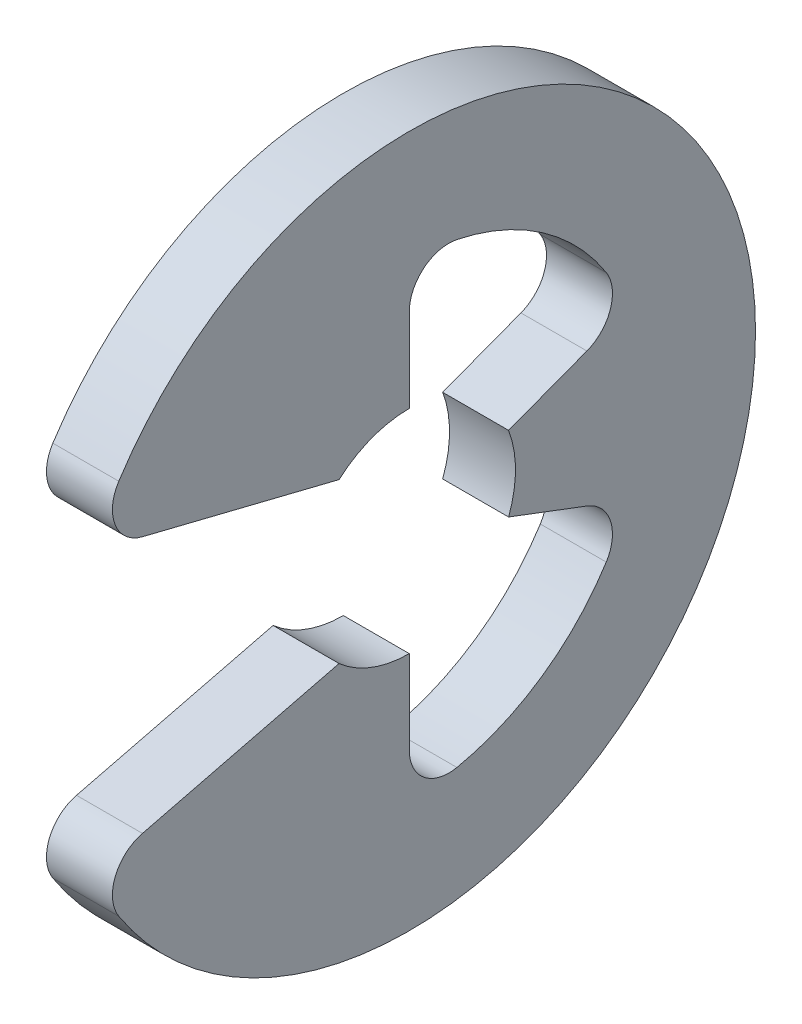
SolidWorks part; units mm, degrees
ref_plane "Front Plane" through (0, 0, 0) normal (0, 0, 1) x (1, 0, 0)
ref_plane "Top Plane" through (0, 0, 0) normal (0, 1, 0) x (1, 0, 0)
ref_plane "Right Plane" through (0, 0, 0) normal (1, 0, 0) x (0, 0, -1)
ref_plane "Plane1" through (-0.25, 0, 0) normal (-1, 0, 0) x (0, -1, 0)
sketch "Sketch1" plane through (-0.25, 0, 0) normal (-1, 0, 0) x (0, -1, 0)
  line L0 (0.9738, 2.023) -> (0.6037, 0.5325)
  line L1 (0.805, 0) -> (1.4394, 0)
  line L2 (0.5089, -1.3464) -> (0.2846, -0.753)
  line L3 (-0.2846, -0.753) -> (-0.5089, -1.3464)
  line L4 (-1.4394, 0) -> (-0.805, 0)
  line L5 (-0.6037, 0.5325) -> (-0.9738, 2.023)
  arc A0 (-1.4282, 2.2025) -> (1.4282, 2.2025) centre (0, 0) ccw
  arc A1 (1.4282, 2.2025) -> (0.9738, 2.023) centre (1.265, 1.9508) ccw
  arc A2 (0.6037, 0.5325) -> (0.805, 0) centre (0, 0) cw
  arc A3 (1.4394, 0) -> (1.7331, -0.3612) centre (1.4394, -0.3) cw
  arc A4 (1.7331, -0.3612) -> (0.9506, -1.4934) centre (0, 0) cw
  arc A5 (0.9506, -1.4934) -> (0.5089, -1.3464) centre (0.7895, -1.2404) cw
  arc A6 (0.2846, -0.753) -> (-0.2846, -0.753) centre (0, 0) cw
  arc A7 (-0.5089, -1.3464) -> (-0.9506, -1.4934) centre (-0.7895, -1.2404) cw
  arc A8 (-0.9506, -1.4934) -> (-1.7331, -0.3612) centre (0, 0) cw
  arc A9 (-1.7331, -0.3612) -> (-1.4394, 0) centre (-1.4394, -0.3) cw
  arc A10 (-0.805, 0) -> (-0.6037, 0.5325) centre (0, 0) cw
  arc A11 (-0.9738, 2.023) -> (-1.4282, 2.2025) centre (-1.265, 1.9508) ccw
  point P25 (0, 0)
  dimension "D1" = 2.625
  dimension "D2" = 0.3
  dimension "D3" = 0.805
  dimension "D4" = 0.3
  dimension "D5" = 1.7703
  dimension "D6" = 0.3
  dimension "D7" = 0.805
  dimension "D8" = 0.3049
  dimension "D9" = 0.7593
  dimension "D10" = 0.7825
  dimension "D11" = 1.2242
extrude "Boss-Extrude1" add sketch "Sketch1" against normal blind 0.5
